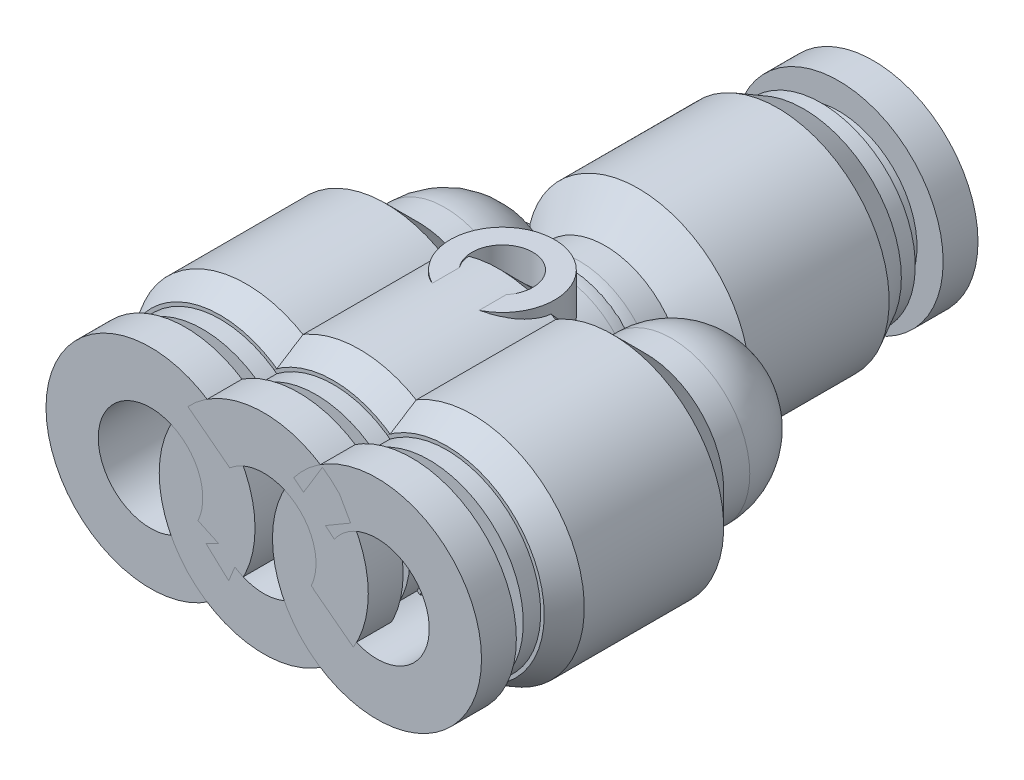
SolidWorks part; units mm, degrees
ref_plane "前视基准面" through (0, 0, 0) normal (0, 0, 1) x (1, 0, 0)
ref_plane "上视基准面" through (0, 0, 0) normal (0, 1, 0) x (1, 0, 0)
ref_plane "右视基准面" through (0, 0, 0) normal (1, 0, 0) x (0, 0, -1)
sketch "草图1" plane through (0, 0, 0) normal (0, 1, 0) x (1, 0, 0)
  line L0 (0, 8.6324) -> (0, -16.4324) construction
  line L1 (4.5, 0.6) -> (4.5, 2.1)
  line L2 (4.5, 2.1) -> (6.4, 4)
  line L3 (6.4, 4) -> (6.4, 12)
  line L4 (6.4, 12) -> (5.6, 13.5)
  line L5 (5.6, 13.5) -> (5.4, 13.5)
  line L6 (5.4, 13.5) -> (5.4, 14.5)
  line L7 (5.4, 14.5) -> (4.5, 14.5)
  line L8 (4.5, 14.5) -> (4.5, 15.5)
  line L9 (4.5, 15.5) -> (6, 15.5)
  line L10 (6, 15.5) -> (6, 17.5)
  line L11 (6, 17.5) -> (3, 17.5)
  line L12 (3, 17.5) -> (3, 7.5)
  line L13 (3, 7.5) -> (0, 7.5)
  line L14 (0, 7.5) -> (0, -3.9)
  arc A0 (0, -3.9) -> (4.5, 0.6) centre (0, 0.6) ccw
  point P4 (0, -3.9)
  dimension "D1" = 9
  dimension "D2" = 6
  dimension "D3" = 135
  dimension "D4" = 8
  dimension "D5" = 1.5
  dimension "D6" = 1
  dimension "D7" = 0.2
  dimension "D8" = 12.8
  dimension "D9" = 1
  dimension "D10" = 1
  dimension "D11" = 2
  dimension "D12" = 9
  dimension "D13" = 12
  dimension "D14" = 6
  dimension "D15" = 10
  dimension "D16" = 3.9
revolve "旋转1" add sketch "草图1" angle 360 about L0
mirror "镜向1" about plane through (0, 0, 0) normal (0, 0, 1) of bodies 106
pattern_linear "阵列(线性)1" count 2 spacing 6.5 along (-1, 0, 0) count 2 spacing 6.5 along (1, 0, 0) of bodies 107
sketch "草图2" plane through (0, 0, 0) normal (0, 1, 0) x (1, 0, 0)
  line L0 (6.4, 4) -> (10, -1.4)
  line L1 (0, 4.0568) -> (0, -4.0568) construction
  line L2 (-10, -1.4) -> (-6.4, 4)
  line L3 (6.4, 4) -> (-6.4, 4)
  line L4 (10, -1.4) -> (-10, -1.4)
  line L7 (-6.4, 4) -> (6.4, 4) construction
  point P14 (0, 0)
  dimension "D1" = 12.8
  dimension "D2" = 20
  dimension "D3" = 5.4
extrude "凸台-拉伸1" add sketch "草图2" along normal mid plane 3
sketch "草图3" plane through (0, 0, 0) normal (0, 1, 0) x (1, 0, 0)
  circle A0 centre (0, -3.8) radius 3
  circle A1 centre (0, -3.8) radius 1.75
  dimension "D1" = 6
  dimension "D3" = 3.5
  dimension "D2" = 3.8
extrude "凸台-拉伸2" add sketch "草图3" along normal mid plane 12.5
sketch "草图4" plane through (0, 6.25, 0) normal (0, 1, 0) x (1, 0, 0)
  circle A0 centre (0, -3.8) radius 1.75 construction
  circle A1 centre (0, -3.8) radius 1.75
extrude "切除-拉伸1" cut sketch "草图4" against normal through all
